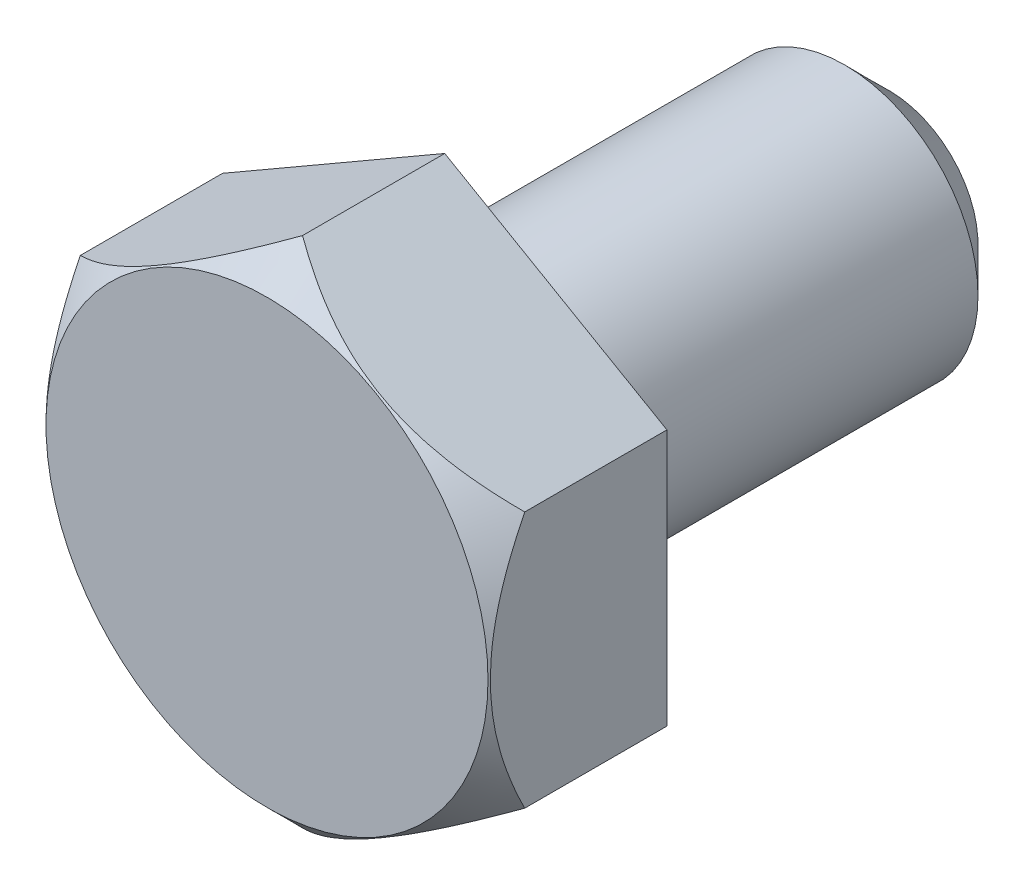
SolidWorks part; units mm, degrees
ref_plane "Спереди" through (0, 0, 0) normal (0, 0, 1) x (1, 0, 0)
ref_plane "Сверху" through (0, 0, 0) normal (0, 1, 0) x (1, 0, 0)
ref_plane "Справа" through (0, 0, 0) normal (1, 0, 0) x (0, 0, -1)
sketch "Эскиз1" plane through (0, 0, 0) normal (0, 0, 1) x (1, 0, 0)
  line L0 (0, 4.93) -> (0, -5.4719) construction
  line L1 (-5.0323, 0) -> (5.1026, 0) construction
  line L3 (0, 5.7735) -> (-5, 2.8868)
  line L4 (-5, 2.8868) -> (-5, -2.8868)
  line L5 (-5, -2.8868) -> (0, -5.7735)
  line L6 (0, -5.7735) -> (5, -2.8868)
  line L7 (5, -2.8868) -> (5, 2.8868)
  line L8 (5, 2.8868) -> (0, 5.7735)
  circle A0 centre (0, 0) radius 5 construction
extrude "Вытянуть1" add sketch "Эскиз1" along normal blind 4
sketch "Эскиз2" plane through (0, 0, 0) normal (0, 0, -1) x (-1, 0, 0)
  circle A0 centre (0, 0) radius 3
extrude "Вытянуть2" add sketch "Эскиз2" along normal blind 10
ref_axis "Ось4" through (0, 0, 2.4653) along (0, 0, -1)
sketch "Эскиз15" plane through (0, 0, 0) normal (1, 0, 0) x (0, 0, -1)
  line L0 (-4, 5.7735) -> (-4, 4.9735)
  line L1 (-4, 2.8868) -> (-4, 5.7735) construction
  line L2 (-4, 4.9735) -> (-3.2, 5.7735)
  line L3 (-4, 5.7735) -> (0, 5.7735) construction
  line L4 (-3.2, 5.7735) -> (-4, 5.7735)
revolve "Вырез-Повернуть1" cut sketch "Эскиз15" angle 360 about axis through (0, 0, 2.4653) along (0, 0, -1)
ref_plane "Плоскость1" through (0, 0, 0) normal (0, -1, 0) x (1, 0, 0)
chamfer "Фаска1" distance 1 angle 45 1 edges at (-3, 0, -10)
